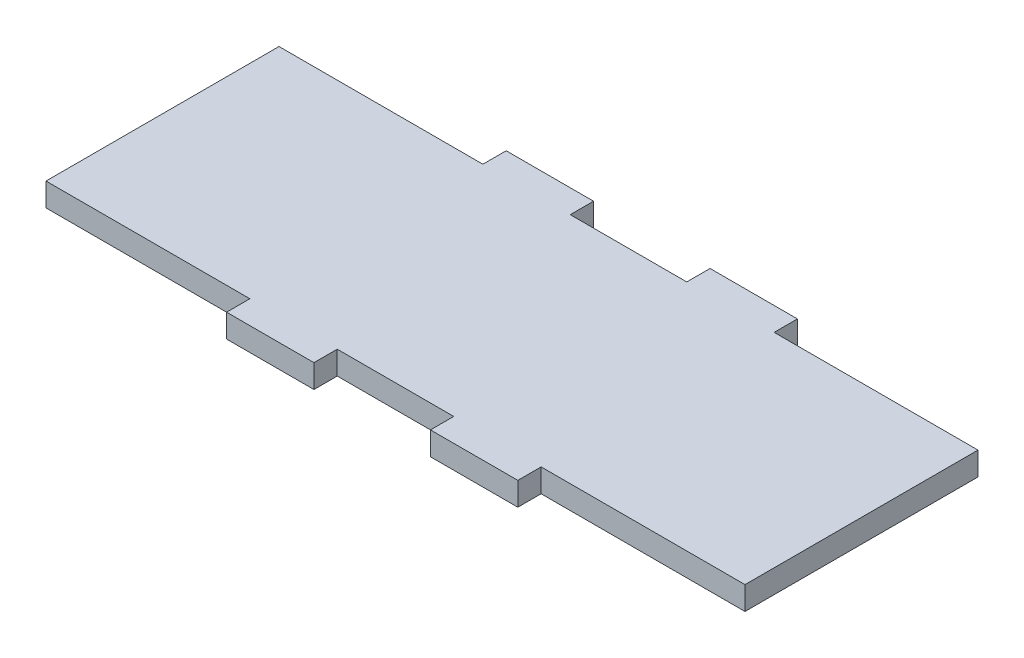
SolidWorks part; units mm, degrees
ref_plane "Front Plane" through (0, 0, 0) normal (0, 0, 1) x (1, 0, 0)
ref_plane "Top Plane" through (0, 0, 0) normal (0, 1, 0) x (1, 0, 0)
ref_plane "Right Plane" through (0, 0, 0) normal (1, 0, 0) x (0, 0, -1)
sketch "Sketch1" plane through (0, 0, 0) normal (0, 0, 1) x (1, 0, 0)
  line L1 (-60, 2) -> (60, 2)
  line L2 (-60, 2) -> (-60, -2)
  line L3 (-60, -2) -> (60, -2)
  line L4 (60, 2) -> (60, -2)
  line L5 (-60, 2) -> (60, -2) construction
  line L6 (-60, -2) -> (60, 2) construction
  point P0 (3.5316, -2.7738)
  dimension "D1" = 4
  dimension "D2" = 120
extrude "Boss-Extrude1" add sketch "Sketch1" along normal blind 48
sketch "Sketch2" plane through (0, -2, 0) normal (0, -1, 0) x (1, 0, 0)
  line L0 (2.2, 0) -> (-2.2, 0) construction
  line L1 (-25, 48) -> (-10, 48)
  line L2 (-25, 48) -> (-25, 44)
  line L3 (-25, 44) -> (-10, 44)
  line L4 (-10, 48) -> (-10, 44)
  line L5 (10, 48) -> (25, 48)
  line L6 (10, 48) -> (10, 44)
  line L7 (10, 44) -> (25, 44)
  line L8 (25, 48) -> (25, 44)
  line L9 (-25, 0) -> (-10, 0)
  line L10 (-25, 0) -> (-25, 4)
  line L11 (-25, 4) -> (-10, 4)
  line L12 (-10, 0) -> (-10, 4)
  line L13 (10, 0) -> (25, 0)
  line L14 (10, 0) -> (10, 4)
  line L15 (10, 4) -> (25, 4)
  line L16 (25, 0) -> (25, 4)
  line L17 (-60, 48) -> (60, 48) construction
  line L18 (0, -2.2) -> (0, 2.2) construction
  line L19 (-60, 48) -> (-60, 0) construction
  line L20 (-60, 44) -> (60, 44)
  line L21 (-60, 44) -> (-60, 4)
  line L22 (-60, 4) -> (60, 4)
  line L23 (60, 44) -> (60, 4)
  line L24 (60, 48) -> (60, 0) construction
  line M21 (-60, 0) -> (60, 0)
  line M22 (60, 0) -> (60, 48)
  line M23 (60, 48) -> (-60, 48)
  line M24 (-60, 48) -> (-60, 0)
  dimension "D1" = 10
  dimension "D2" = 15
  dimension "D3" = 4
  dimension "D4" = 15
  dimension "D5" = 10
  dimension "D6" = 4
  dimension "D7" = 15
  dimension "D8" = 15
  dimension "D9" = 10
extrude "Cut-Extrude1" cut sketch "Sketch2" against normal blind 48 contours L20 L2 M24 M23 | L4 L20 L6 M23 | L8 L20 M22 M23 | L22 L16 M21 M22 | L22 L12 L14 M21 | L22 L10 M24 M21
